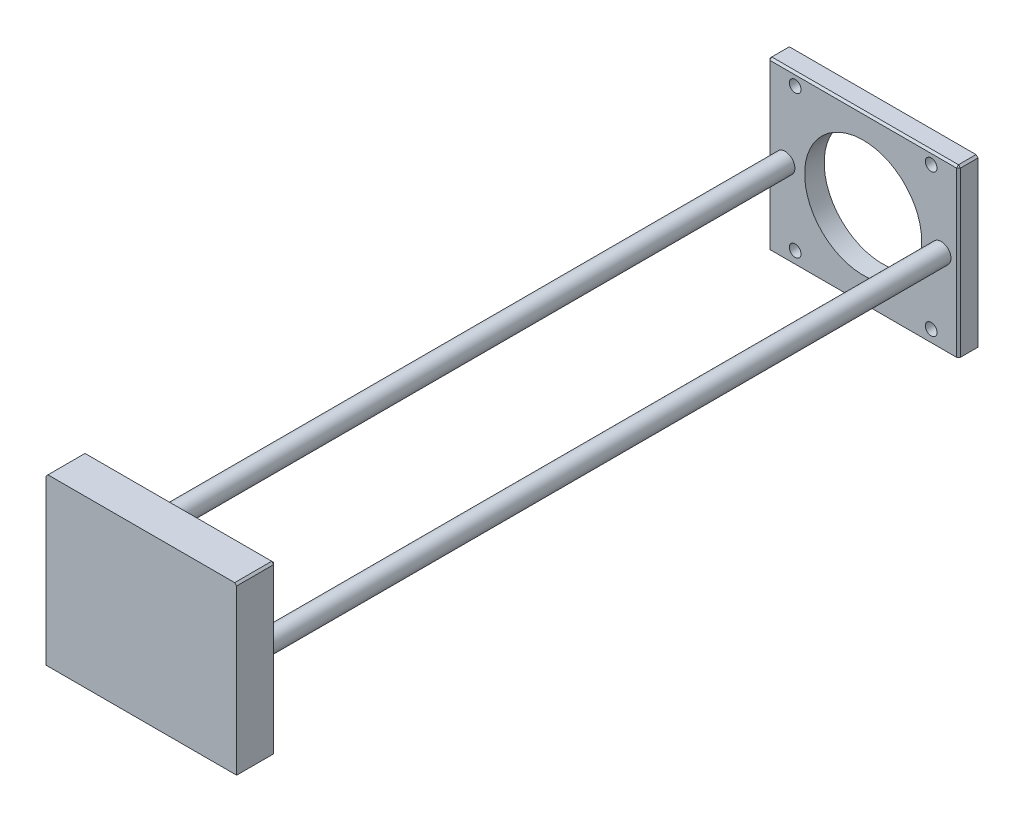
SolidWorks part; units mm, degrees
ref_plane "Alzado" through (0, 0, 0) normal (0, 0, 1) x (1, 0, 0)
ref_plane "Planta" through (0, 0, 0) normal (0, 1, 0) x (1, 0, 0)
ref_plane "Vista lateral" through (0, 0, 0) normal (1, 0, 0) x (0, 0, -1)
sketch "Croquis1" plane through (0, 0, 0) normal (0, 0, 1) x (1, 0, 0)
  line L0 (-34.85, 42.5) -> (-34.85, 36.5) construction
  line L1 (48.85, -42.5) -> (-48.85, -42.5)
  line L2 (48.85, -42.5) -> (48.85, 42.5)
  line L3 (48.85, 42.5) -> (-48.85, 42.5)
  line L4 (-48.85, -42.5) -> (-48.85, 42.5)
  line L5 (48.85, -42.5) -> (-48.85, 42.5) construction
  line L6 (48.85, 42.5) -> (-48.85, -42.5) construction
  line L7 (-34.85, 36.5) -> (-48.85, 36.5) construction
  line L8 (0, 42.5) -> (0, -42.5) construction
  line L9 (-48.85, 0) -> (48.85, 0) construction
  circle A0 centre (-34.85, 36.5) radius 3
  circle A1 centre (0, 0) radius 30
  circle A2 centre (34.85, 36.5) radius 3
  circle A3 centre (34.85, -36.5) radius 3
  circle A4 centre (-34.85, -36.5) radius 3
  point P0 (0, 0)
  dimension "D5" = 6
  dimension "D6" = 60
  dimension "D1" = 97.7
  dimension "D2" = 85
  dimension "D3" = 6
  dimension "D4" = 14
extrude "Saliente-Extruir1" add sketch "Croquis1" along normal blind 10
sketch "Croquis2" plane through (0, 0, 10) normal (0, 0, 1) x (1, 0, 0)
  line L0 (-34.85, 36.5) -> (-34.85, -36.5) construction
  line L1 (34.85, 36.5) -> (34.85, -36.5) construction
  line L3 (0, 42.5) -> (0, -42.5) construction
  line L4 (48.85, 42.5) -> (-48.85, 42.5) construction
  line L5 (-48.85, -42.5) -> (48.85, -42.5) construction
  circle A1 centre (-40, 0) radius 5
  circle A2 centre (40, 0) radius 5
  point P15 (0, 0)
  dimension "D1" = 10
  dimension "D2" = 40
extrude "Saliente-Extruir2" add sketch "Croquis2" along normal blind 350
ref_plane "Plano1" through (0, 0, 360) normal (0, 0, 1) x (1, 0, 0)
sketch "Croquis3" plane through (0, 0, 360) normal (0, 0, 1) x (1, 0, 0)
  line L1 (-48.85, 42.5) -> (48.85, 42.5)
  line L2 (-48.85, 42.5) -> (-48.85, -42.5)
  line L3 (-48.85, -42.5) -> (48.85, -42.5)
  line L4 (48.85, 42.5) -> (48.85, -42.5)
extrude "Saliente-Extruir3" add sketch "Croquis3" along normal blind 20
chamfer "Chaflán1" distance 1 angle 45 10 edges at (-48.85, 42.5, 5) (48.85, 42.5, 5) (-48.85, 0, 10) (48.85, 0, 10) (0, 42.5, 10) (-48.85, 0, 360) (48.85, 0, 360) (-48.85, 42.5, 370) (48.85, 42.5, 370) (0, 42.5, 360)
